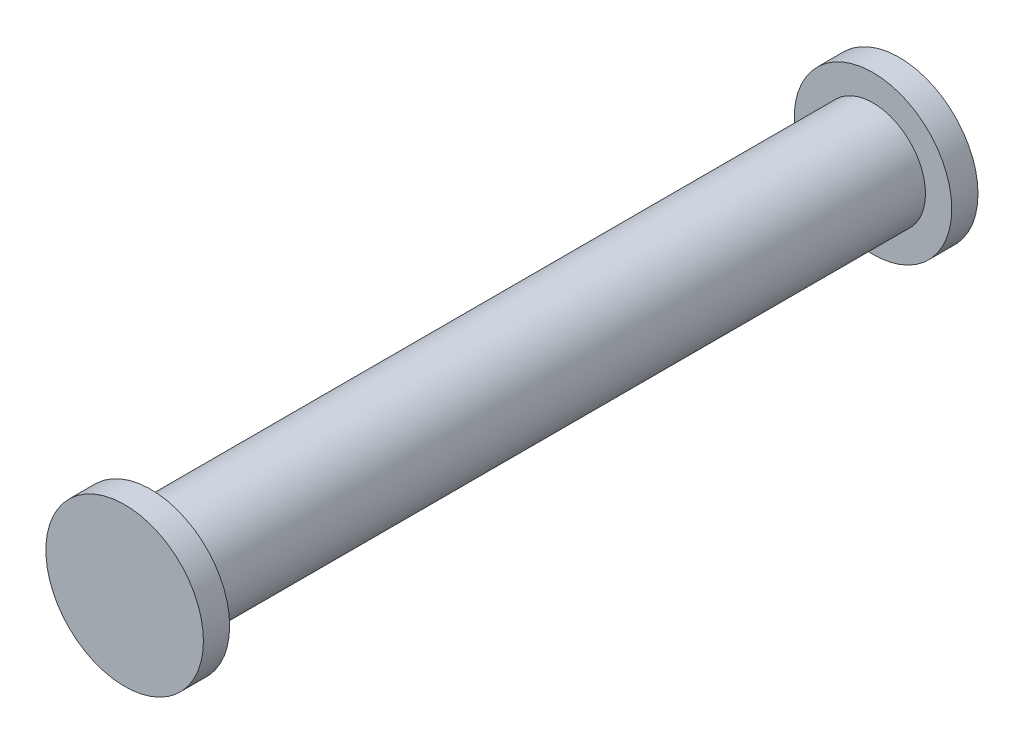
SolidWorks part; units mm, degrees
ref_plane "Alzado" through (0, 0, 0) normal (0, 0, 1) x (1, 0, 0)
ref_plane "Planta" through (0, 0, 0) normal (0, 1, 0) x (1, 0, 0)
ref_plane "Vista lateral" through (0, 0, 0) normal (1, 0, 0) x (0, 0, -1)
sketch "Croquis1" plane through (0, 0, 0) normal (0, 0, 1) x (1, 0, 0)
  circle A0 centre (0, 0) radius 4
  dimension "D1" = 8
extrude "Saliente-Extruir1" add sketch "Croquis1" along normal mid plane 55
sketch "Croquis2" plane through (0, 0, 27.5) normal (0, 0, 1) x (1, 0, 0)
  circle A0 centre (0, 0) radius 6
  dimension "D1" = 12
extrude "Saliente-Extruir2" add sketch "Croquis2" along normal blind 2
mirror "Simetría1" about plane through (0, 0, 0) normal (0, 0, 1) of "Saliente-Extruir2"
